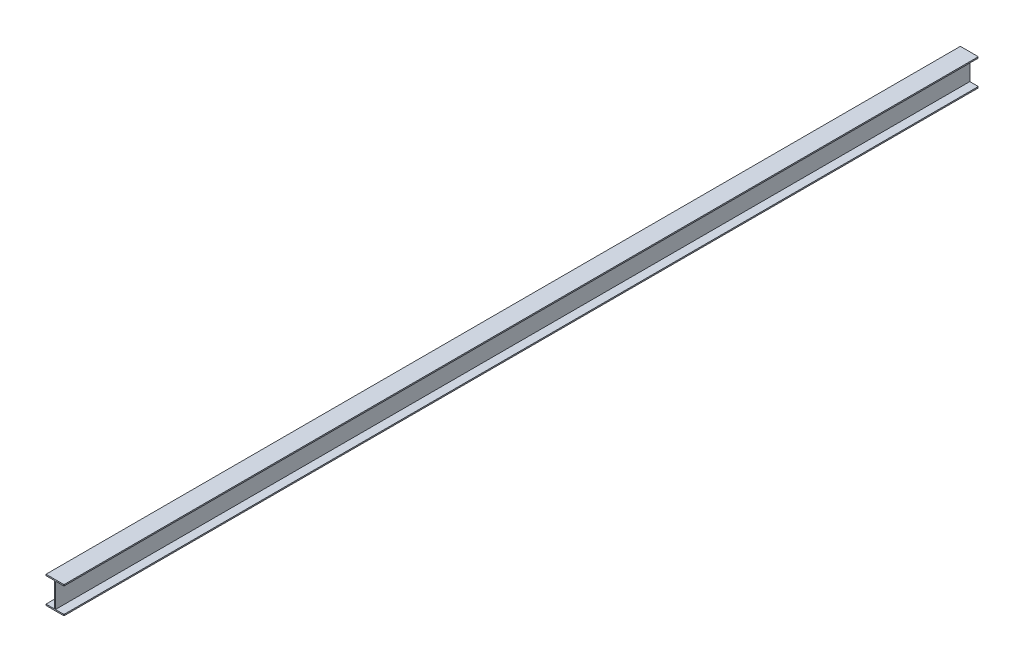
SolidWorks part; units mm, degrees
material "ASTM A992 Steel"
ref_plane "Front" through (0, 0, 0) normal (0, 0, 1) x (1, 0, 0)
ref_plane "Top" through (0, 0, 0) normal (0, 1, 0) x (1, 0, 0)
ref_plane "Right" through (0, 0, 0) normal (1, 0, 0) x (0, 0, -1)
sketch "Sketch1" plane through (0, 0, 0) normal (0, 0, 1) x (1, 0, 0)
  line L0 (0, -0.0002) -> (101.6, -0.0002)
  line L1 (101.6, -0.0002) -> (101.6, -7.1122)
  line L2 (101.6, -7.1122) -> (53.408, -7.1122)
  line L3 (53.408, -7.1122) -> (53.408, -146.0502)
  line L4 (53.408, -146.0502) -> (101.6, -146.0502)
  line L5 (101.6, -146.0502) -> (101.6, -153.1622)
  line L6 (101.6, -153.1622) -> (0, -153.1622)
  line L7 (0, -153.1622) -> (0, -146.0502)
  line L8 (0, -146.0502) -> (47.566, -146.0502)
  line L9 (47.566, -146.0502) -> (47.566, -7.1122)
  line L10 (47.566, -7.1122) -> (0, -7.1122)
  line L11 (0, -7.1122) -> (0, -0.0002)
  line L12 (50.8, -0.0002) -> (50.8, -153.1622) construction
  dimension "D1" = 5.842
  dimension "D2" = 7.112
  dimension "D3" = 7.112
  dimension "D4" = 7.112
  dimension "D5" = 153.162
  dimension "D6" = 50.8
  dimension "D7" = 50.8
  dimension "D8" = 47.566
extrude "Boss-Extrude1" add sketch "Sketch1" along normal blind 5168.8161
sketch "Sketch2" plane through (0, -153.1622, 0) normal (0, -1, 0) x (1, 0, 0)
  line L0 (0, 5168.8161) -> (0, 0) construction
  line L1 (101.6, 5168.8161) -> (101.6, 0) construction
  line L3 (101.6, 2584.408) -> (101.6, 2736.808)
  line L4 (101.6, 2736.808) -> (-279.5172, 2736.808)
  line L5 (-279.5172, 2607.2) -> (-279.5172, 2736.808)
  line L8 (101.6, 2584.408) -> (101.6, 2432.008)
  line L9 (101.6, 2432.008) -> (-279.5172, 2432.008)
  line L10 (-279.5172, 2607.2) -> (-279.5172, 2432.008)
  point P0 (0, 2584.408)
  dimension "D1" = 152.4
  dimension "D2" = 152.4
split line "Split Line1"
fillet "Fillet1" radius 3.175 4 edges at (101.6, -3.5562, 5168.8161) (101.6, -149.6062, 5168.8161) (101.6, -149.6062, 0) (101.6, -3.5562, 0)
